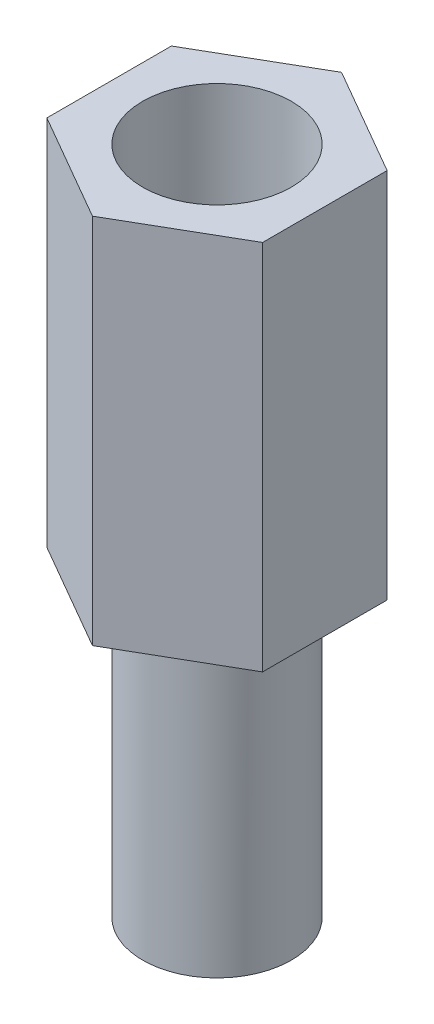
SolidWorks part; units mm, degrees
material "黄铜"
ref_plane "前视基准面" through (0, 0, 0) normal (0, 0, 1) x (1, 0, 0)
ref_plane "上视基准面" through (0, 0, 0) normal (0, 1, 0) x (1, 0, 0)
ref_plane "右视基准面" through (0, 0, 0) normal (1, 0, 0) x (0, 0, -1)
other "Configuration Table"
sketch "草图1" plane through (0, 0, 0) normal (0, 1, 0) x (1, 0, 0)
  line L1 (0, 1.6743) -> (-1.45, 0.8372)
  line L2 (-1.45, 0.8372) -> (-1.45, -0.8372)
  line L3 (-1.45, -0.8372) -> (0, -1.6743)
  line L4 (0, -1.6743) -> (1.45, -0.8372)
  line L5 (1.45, -0.8372) -> (1.45, 0.8372)
  line L6 (1.45, 0.8372) -> (0, 1.6743)
  circle A0 centre (0, 0) radius 1
  circle A1 centre (0, 0) radius 1.45 construction
  dimension "D1" = 2
  dimension "D2" = 2.9
extrude "凸台-拉伸1" add sketch "草图1" along normal blind 5
sketch "草图2" plane through (0, 0, 0) normal (0, -1, 0) x (1, 0, 0)
  circle A0 centre (0, 0) radius 1
  dimension "D1" = 2
extrude "凸台-拉伸2" add sketch "草图2" along normal blind 4 and the other way blind 2
